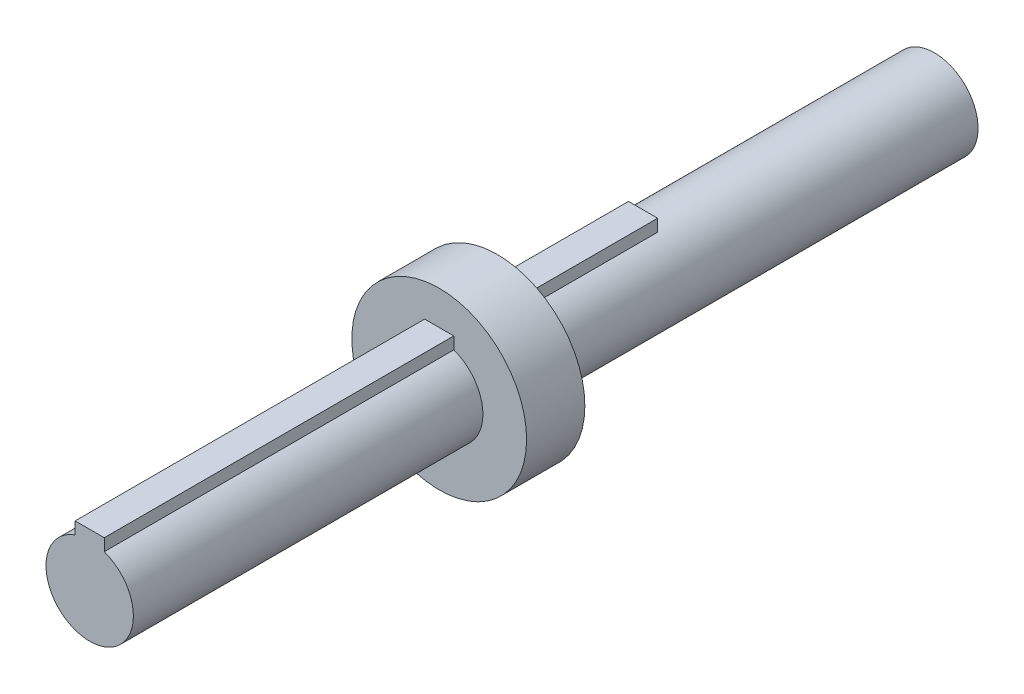
SolidWorks part; units mm, degrees
material "Galvanized Steel"
ref_plane "Front Plane" through (0, 0, 0) normal (0, 0, 1) x (1, 0, 0)
ref_plane "Top Plane" through (0, 0, 0) normal (0, 1, 0) x (1, 0, 0)
ref_plane "Right Plane" through (0, 0, 0) normal (1, 0, 0) x (0, 0, -1)
sketch "Sketch1" plane through (0, 0, 0) normal (0, 0, 1) x (1, 0, 0)
  line L0 (-5, 14.1421) -> (-5, 18.3)
  line L1 (5, 18.3) -> (5, 14.1421)
  line L2 (-5, 18.3) -> (5, 18.3)
  arc A0 (-5, 14.1421) -> (5, 14.1421) centre (0, 0) ccw
  dimension "D1" = 15
  dimension "D2" = 10
  dimension "D3" = 18.3
  dimension "D4" = 5
extrude "Boss-Extrude1" add sketch "Sketch1" along normal mid plane 1600
sketch "Sketch2" plane through (0, 0, -800) normal (0, 0, -1) x (-1, 0, 0)
  circle A0 centre (0, 0) radius 25
  dimension "D1" = 50
extrude "Boss-Extrude2" [suppressed] add sketch "Sketch2" along normal mid plane 10
ref_plane "Plane1" through (0, 0, 590) normal (0, 0, 1) x (1, 0, 0)
sketch "Sketch3" plane through (0, 0, 590) normal (0, 0, -1) x (-1, 0, 0)
  circle A0 centre (0, 0) radius 30
  dimension "D1" = 60
extrude "Boss-Extrude3" add sketch "Sketch3" against normal blind 20
mirror "Mirror2" about plane through (0, 0, 0) normal (0, 0, 1) of "Boss-Extrude3"
sketch "Sketch4" plane through (0, 0, -590) normal (0, 0, 1) x (1, 0, 0)
  circle A1 centre (0, 0) radius 30
  circle A2 centre (0, 0) radius 30
  dimension "D1" = 0
extrude "Cut-Extrude1" cut sketch "Sketch4" along normal through all
sketch "Sketch5" plane through (0, 0, -800) normal (0, 0, -1) x (-1, 0, 0)
  circle A0 centre (0, 0) radius 15
  dimension "D1" = 30
extrude "Boss-Extrude4" add sketch "Sketch5" along normal blind 100
sketch "Sketch6" plane through (0, 0, -590) normal (0, 0, 1) x (1, 0, 0)
  circle A1 centre (0, 0) radius 30
  circle A2 centre (0, 0) radius 30
  dimension "D1" = 0
extrude "Cut-Extrude2" cut sketch "Sketch6" against normal blind 20
sketch "Sketch7" plane through (0, 0, -610) normal (0, 0, 1) x (1, 0, 0)
  circle A1 centre (0, 0) radius 30
  circle A2 centre (0, 0) radius 30
  dimension "D1" = 0
extrude "Boss-Extrude5" add sketch "Sketch7" along normal blind 20 from offset 140 offset against normal yes
